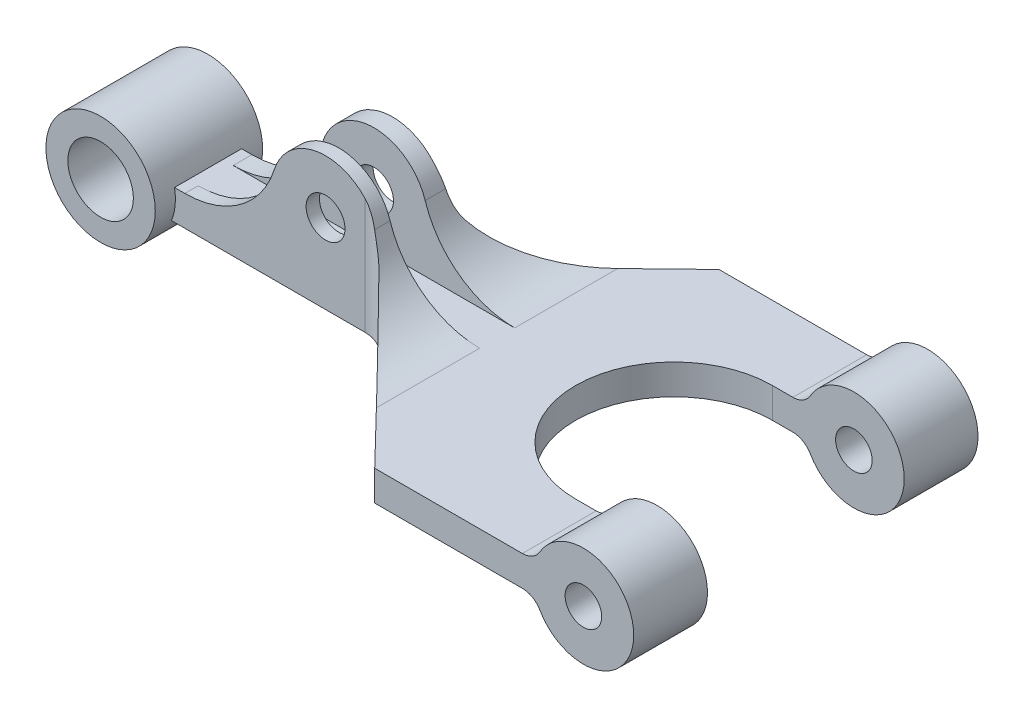
SolidWorks part; units mm, degrees
material "Cast Carbon Steel"
ref_plane "Front Plane" through (0, 0, 0) normal (0, 0, 1) x (1, 0, 0)
ref_plane "Top Plane" through (0, 0, 0) normal (0, 1, 0) x (1, 0, 0)
ref_plane "Right Plane" through (0, 0, 0) normal (1, 0, 0) x (0, 0, -1)
other "Configuration Table"
sketch "Sketch1" plane through (0, 0, 0) normal (0, 0, 1) x (1, 0, 0)
  circle A0 centre (12.7411, -63.1344) radius 2.9
  circle A1 centre (12.7411, -63.1344) radius 8
extrude "Extrude1" add sketch "Sketch1" against normal blind 10
ref_plane "Plane4" through (0, -71, 0) normal (0, 1, 0) x (-1, 0, 0)
sketch "Sketch2" plane through (0, -71, 0) normal (0, 1, 0) x (-1, 0, 0)
  line L0 (-12.7411, 0) -> (12.9084, 0)
  line L1 (-9.8411, 0) -> (-15.6411, 0) construction
  line L2 (12.9084, 0) -> (12.9084, -10)
  line L3 (12.9084, -10) -> (-12.7411, -10)
  line L4 (-20.7411, -10) -> (-4.7411, -10) construction
  line L5 (-12.7411, -10) -> (-20.7411, -10)
  line L6 (-20.7411, -10) -> (-41.3922, -30)
  line L7 (-60.3431, 10.3234) -> (-65.3431, 10.3234)
  line L8 (-65.3431, -19) -> (-60.3431, -19)
  line L9 (-41.3922, 21.3234) -> (-65.3431, 21.3234)
  line L10 (-41.3922, -30) -> (-65.3431, -30)
  line L11 (-65.3431, -30) -> (-65.3431, -19)
  line L12 (-65.3431, 21.3234) -> (-65.3431, 10.3234)
  line L13 (-20.7411, 0) -> (-41.3922, 21.3234)
  line L14 (-60.3431, 10.3234) -> (-60.3431, -19) construction
  line L16 (-20.7411, 0) -> (-12.7411, 0)
  arc A0 (-60.3431, -19) -> (-60.3431, 10.3234) centre (-60.3431, -4.3383) ccw
  dimension "D1" = 11
  dimension "D5" = 20
  dimension "D6" = 11
extrude "Extrude2" add sketch "Sketch2" along normal blind 0.5 and the other way blind 4
sketch "Sketch4" plane through (0, 0, 0) normal (1, 0, 0) x (0, 0, -1)
  line L1 (1.9919, -52.3482) -> (7.2199, -52.3482)
  line L2 (1.9919, -52.3482) -> (1.9919, -70.5)
  line L3 (1.9919, -70.5) -> (7.2199, -70.5)
  line L4 (7.2199, -52.3482) -> (7.2199, -70.5)
extrude "Cut-Extrude1" cut sketch "Sketch4" along normal through all
fillet "Fillet4" radius 14 4 edges at (9.6191, -70.5, -0.9959) (15.8632, -70.5, -0.9959) (15.8632, -70.5, -8.6099) (9.6191, -70.5, -8.6099)
sketch "Sketch6" plane through (0, 0, 21.3234) normal (0, 0, 1) x (1, 0, 0)
  circle A0 centre (72.4977, -72.75) radius 2.7266
  circle A1 centre (72.4977, -72.75) radius 7.5
extrude "Extrude4" add sketch "Sketch6" against normal blind 11
ref_plane "Plane5" [suppressed] through (0, 0, -10) normal (0, 0, 1) x (1, 0, 0)
sketch "Sketch8" plane through (0, 0, -30) normal (0, 0, 1) x (1, 0, 0)
  circle A0 centre (72.4977, -72.75) radius 7.5
  circle A1 centre (72.4977, -72.75) radius 2.725
sketch "Sketch11" plane through (0, 0, 0) normal (0, 0, 1) x (1, 0, 0)
  circle A0 centre (-17.7936, -71.9602) radius 8.1518
  circle A1 centre (-17.7936, -71.9602) radius 4.8851
extrude "Extrude6" add sketch "Sketch11" against normal blind 13 and the other way blind 3
extrude "Extrude7" add sketch "Sketch8" along normal blind 11
fillet "Fillet19" radius 3 4 edges at (65.3431, -75, 15.8234) (65.3431, -70.5, 15.8234) (65.3431, -75, -24.5) (65.3431, -70.5, -24.5)
fillet "Fillet23" radius 5 2 edges at (20.7411, -68.3781, -10) (20.7411, -68.3781, 0)
ref_plane "MidPlane - arm" through (0, 0, -4.6049) normal (0, 0, 1) x (1, 0, 0)
